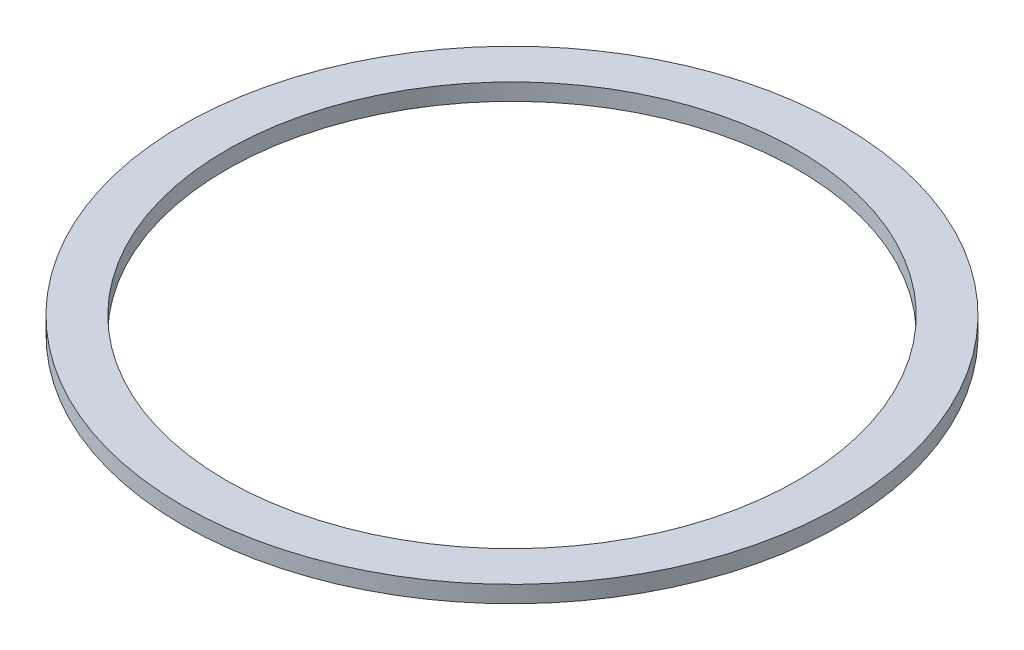
SolidWorks part; units mm, degrees
ref_plane "前视基准面" through (0, 0, 0) normal (0, 0, 1) x (1, 0, 0)
ref_plane "上视基准面" through (0, 0, 0) normal (0, 1, 0) x (1, 0, 0)
ref_plane "右视基准面" through (0, 0, 0) normal (1, 0, 0) x (0, 0, -1)
sketch "草图1" plane through (0, 0, 0) normal (0, 1, 0) x (1, 0, 0)
  circle A0 centre (0, 0) radius 196
  circle A1 centre (0, 0) radius 170
  dimension "D1" = 392
  dimension "D2" = 340
extrude "凸台-拉伸1" add sketch "草图1" along normal blind 10
